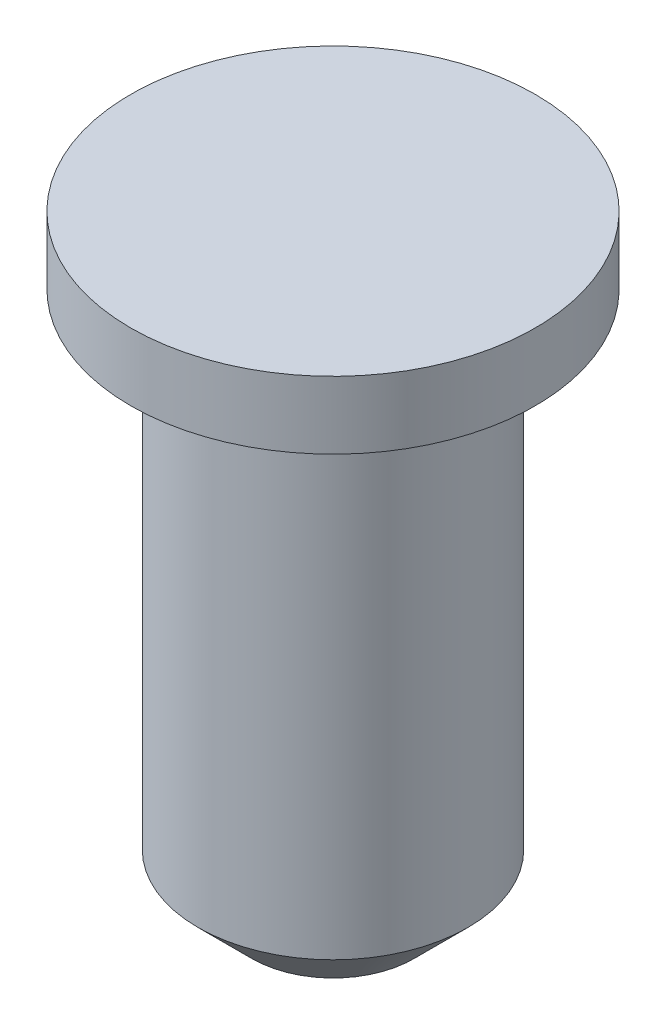
SolidWorks part; units mm, degrees
ref_plane "Front Plane" through (0, 0, 0) normal (0, 0, 1) x (1, 0, 0)
ref_plane "Top Plane" through (0, 0, 0) normal (0, 1, 0) x (1, 0, 0)
ref_plane "Right Plane" through (0, 0, 0) normal (1, 0, 0) x (0, 0, -1)
sketch "Sketch1" plane through (0, 0, 0) normal (0, 1, 0) x (1, 0, 0)
  circle A0 centre (0, 0) radius 2
  dimension "D1" = 4
extrude "Boss-Extrude1" add sketch "Sketch1" along normal blind 8
sketch "Sketch2" plane through (0, 8, 0) normal (0, 1, 0) x (1, 0, 0)
  circle A0 centre (0, 0) radius 3
  dimension "D1" = 6
extrude "Boss-Extrude2" add sketch "Sketch2" along normal blind 1
chamfer "Chamfer1" distance 0.8 angle 45 1 edges at (0, 0, 2)
